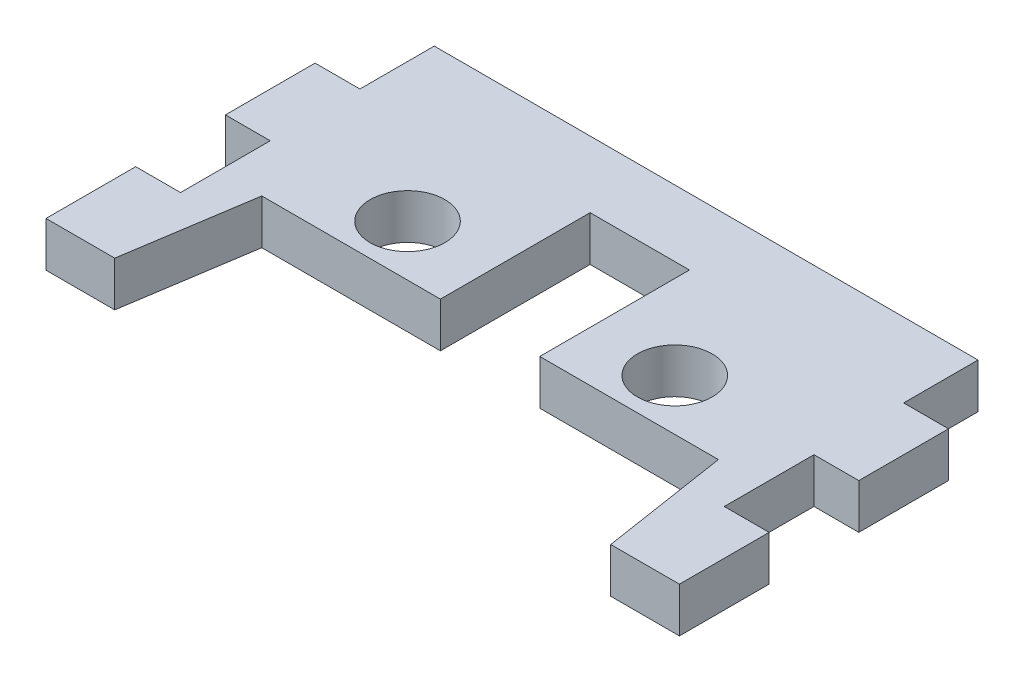
SolidWorks part; units mm, degrees
ref_plane "Front Plane" through (0, 0, 0) normal (0, 0, 1) x (1, 0, 0)
ref_plane "Top Plane" through (0, 0, 0) normal (0, 1, 0) x (1, 0, 0)
ref_plane "Right Plane" through (0, 0, 0) normal (1, 0, 0) x (0, 0, -1)
sketch "Sketch1" plane through (0, 0, 0) normal (0, 1, 0) x (1, 0, 0)
  line L0 (13.6733, -16.6355) -> (4.4782, -16.6355)
  line L1 (4.4782, -16.6355) -> (4.4782, -4.6355)
  line L2 (4.4782, -4.6355) -> (10.4782, -4.6355)
  line L3 (10.4782, -4.6355) -> (10.4782, 7.3645)
  line L4 (10.4782, 7.3645) -> (4.4782, 7.3645)
  line L5 (4.4782, 7.3645) -> (4.4782, 19.3645)
  line L6 (10.4782, 29.3111) -> (83.2254, 29.3111)
  line L7 (89.2254, 7.3645) -> (89.2254, 19.3645)
  line L8 (89.2254, 7.3645) -> (83.2254, 7.3645)
  line L9 (83.2254, 7.3645) -> (83.2254, -4.6355)
  line L10 (83.2254, -4.6355) -> (89.2254, -4.6355)
  line L11 (89.2254, -4.6355) -> (89.2254, -16.6355)
  line L12 (89.2254, -16.6355) -> (80.0304, -16.6355)
  line L13 (80.0304, -16.6355) -> (77.3951, 0.4057)
  line L14 (77.3951, 0.4057) -> (53.4968, 0.4057)
  line L15 (16.3085, 0.4057) -> (13.6733, -16.6355)
  line L16 (4.4782, 19.3645) -> (10.4782, 19.3645)
  line L17 (28.9745, 7.2378) -> (64.7291, 7.2378) construction
  line L18 (40.2069, 0.4057) -> (16.3085, 0.4057)
  line L19 (10.4782, 19.3645) -> (10.4782, 29.3111)
  line L20 (40.2069, 0.4057) -> (40.2069, 20.4324)
  line L21 (40.2069, 20.4324) -> (53.4968, 20.4324)
  line L22 (53.4968, 0.4057) -> (53.4968, 20.4324)
  line L23 (89.2254, 19.3645) -> (83.2254, 19.3645)
  line L24 (83.2254, 19.3645) -> (83.2254, 29.3111)
  circle A0 centre (28.9745, 7.2378) radius 5
  circle A1 centre (64.7291, 7.2378) radius 5
  point P17 (46.8518, 29.3111)
  point P24 (46.8518, 7.2378)
  point P25 (46.8518, 20.4324)
extrude "Boss-Extrude1" add sketch "Sketch1" along normal blind 6
